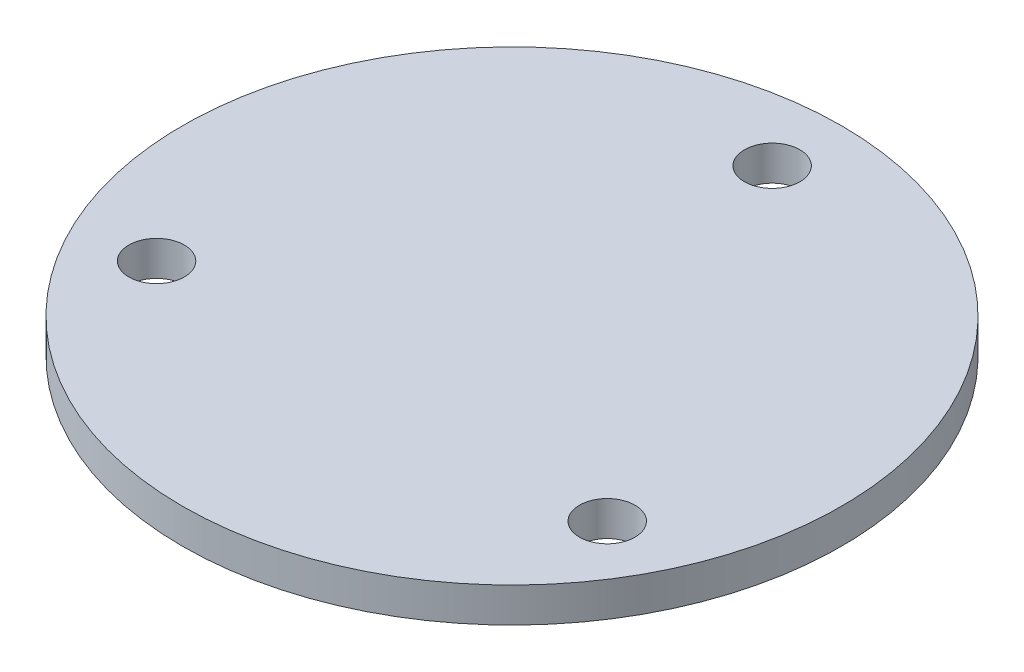
SolidWorks part; units mm, degrees
ref_plane "Front Plane" through (0, 0, 0) normal (0, 0, 1) x (1, 0, 0)
ref_plane "Top Plane" through (0, 0, 0) normal (0, 1, 0) x (1, 0, 0)
ref_plane "Right Plane" through (0, 0, 0) normal (1, 0, 0) x (0, 0, -1)
sketch "Sketch1" plane through (0, 0, 0) normal (0, 1, 0) x (1, 0, 0)
  circle A0 centre (0, 0) radius 19
  circle A1 centre (0, 0) radius 15 construction
  circle A2 centre (0, 15) radius 1.6
  circle A3 centre (12.9904, -7.5) radius 1.6
  circle A4 centre (-12.9904, -7.5) radius 1.6
  dimension "D1" = 38
  dimension "D2" = 30
  dimension "D3" = 3.2
  dimension "D4" = 3
extrude "Boss-Extrude1" add sketch "Sketch1" along normal blind 2
